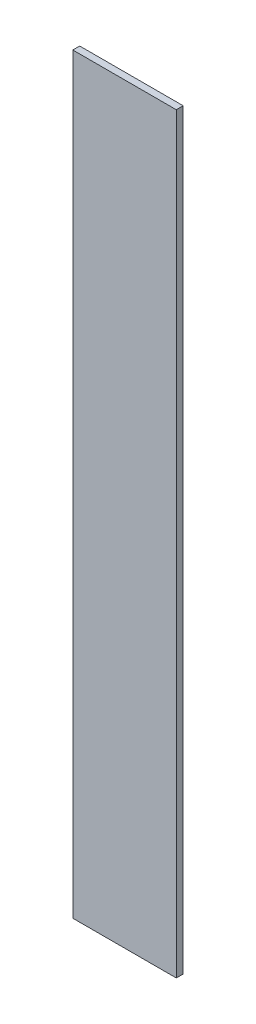
SolidWorks part; units mm, degrees
ref_plane "Front Plane" through (0, 0, 0) normal (0, 0, 1) x (1, 0, 0)
ref_plane "Top Plane" through (0, 0, 0) normal (0, 1, 0) x (1, 0, 0)
ref_plane "Right Plane" through (0, 0, 0) normal (1, 0, 0) x (0, 0, -1)
sketch "Sketch1" plane through (0, 0, 0) normal (0, 0, 1) x (1, 0, 0)
  line L1 (-15, -109) -> (15, -109)
  line L2 (-15, -109) -> (-15, 109)
  line L3 (-15, 109) -> (15, 109)
  line L4 (15, -109) -> (15, 109)
  line L5 (0, 109) -> (0, -109) construction
  line L6 (-15, 0) -> (15, 0) construction
  point P0 (0, 0)
  dimension "D1" = 218
  dimension "D2" = 30
extrude "Boss-Extrude1" add sketch "Sketch1" along normal blind 2
